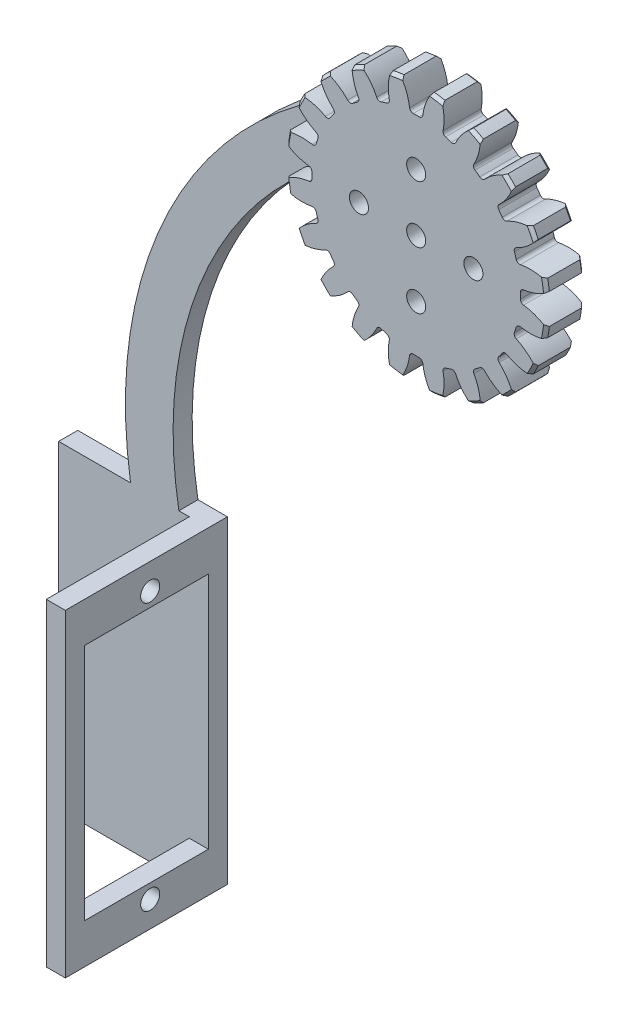
SolidWorks part; units mm, degrees
ref_plane "Front Plane" through (0, 0, 0) normal (0, 0, 1) x (1, 0, 0)
ref_plane "Top Plane" through (0, 0, 0) normal (0, 1, 0) x (1, 0, 0)
ref_plane "Right Plane" through (0, 0, 0) normal (1, 0, 0) x (0, 0, -1)
sketch "Sketch1" plane through (0, 0, 0) normal (0, 0, 1) x (1, 0, 0)
  circle A0 centre (0, 0) radius 12.5 construction
  circle A1 centre (0, 0) radius 13.75
  dimension "D1" = 25
  dimension "D2" = 27.5
extrude "Boss-Extrude1" add sketch "Sketch1" along normal blind 4 contours A1
sketch "Sketch3" plane through (0, 0, 0) normal (0, 0, 1) x (1, 0, 0)
  line L0 (0, 0) -> (0, 13.75) construction
  line L1 (0, 0) -> (-2.151, 13.5807) construction
  line L2 (0, 0) -> (2.151, 13.5807) construction
  line L3 (-2.3599, 10.6799) -> (0, 0) construction
  line L4 (-2.9181, 12.1546) -> (-0.9807, 12.4615) construction
  line L5 (-0.9807, 12.4615) -> (0.9807, 12.4615) construction
  line L6 (-3.5448, 13.2852) -> (-1.5279, 9.6467) construction
  arc A0 (-1.0558, 10.8864) -> (-2.3599, 10.6799) centre (0, 0) ccw
  circle A1 centre (0, 0) radius 11.25 construction
  circle A2 centre (0, 0) radius 13.75 construction
  arc A3 (-3.7081, 13.2406) -> (-2.3599, 10.6799) centre (-7.7122, 9.4972) cw
  circle A4 centre (0, 0) radius 13.75 construction
  arc A5 (-0.5649, 13.7384) -> (-1.0558, 10.8864) centre (4.4, 11.4156) ccw
  circle A6 centre (0, 0) radius 12.5 construction
  arc A7 (-0.5649, 13.7384) -> (-3.7081, 13.2406) centre (0, 0) ccw
  dimension "D1" = 18
  dimension "D2" = 2.5
  dimension "D3" = 2.8125
  dimension "D4" = 20
extrude "Cut-Extrude4" cut sketch "Sketch3" against normal through all and the other way through all
fillet "Fillet1" radius 0.375 2 edges at (-1.0558, 10.8864, 2) (-2.3599, 10.6799, 2)
chamfer "Chamfer1" distance 0.3125 2 edges at (2.151, -13.5807, 0) (2.151, -13.5807, 4)
pattern_circular "CirPattern1" count 20 over 360 about axis through (0, 0, 0) along (0, 0, 1) of "Cut-Extrude4", "Fillet1"
sketch "Sketch4" plane through (0, 0, 4) normal (0, 0, 1) x (1, 0, 0)
  circle A0 centre (0, 0) radius 0.5
extrude "Cut-Extrude5" cut sketch "Sketch4" against normal through all
move or copy body "Body-Move/Copy1" bodies to move or copy 105 copy no rotation origin (0, 0, 0) rotation axis (0, 0, 1) rotation angle 9
mirror "Mirror1" about plane through (0, 0, 0) normal (1, 0, 0) of bodies 108 107
delete or keep bodies "Body-Delete/Keep 1" type delete bodies bodies 108
sketch "Sketch12" plane through (0, 0, 4) normal (0, 0, 1) x (1, 0, 0)
  line L0 (0, -16.1208) -> (0, 16.4837) construction
  line L1 (3.7696, 0) -> (-5.3712, 0) construction
  circle A0 centre (0, 0) radius 1
  circle A1 centre (0, -6) radius 1
  circle A2 centre (-6, 0) radius 1
  circle A3 centre (0, 6) radius 1
  circle A4 centre (6, 0) radius 1
  point P19 (0, 0)
  dimension "D1" = 2
  dimension "D2" = 2
  dimension "D3" = 6
  dimension "D4" = 4
extrude "Cut-Extrude8" cut sketch "Sketch12" against normal up to surface (4 mm away) up to face at (-0.4938, 0.0782, 0)
sketch "Sketch13" plane through (0, 0, 0) normal (0, 0, -1) x (-1, 0, 0)
  line L0 (23.1469, 0) -> (-25.305, 0) construction
  line L1 (21.3966, -32.5) -> (-39.3897, -32.5) construction
  line L2 (-12.5, 6.7605) -> (-12.5, -41.0245) construction
  line L3 (12.5, 6.7605) -> (12.5, -41.0245) construction
  line L4 (23.8, -16.4657) -> (23.8, -36.0763) construction
  line L5 (56.7967, -39.45) -> (45.2507, -39.45) construction
  line L6 (56.7967, -44.45) -> (-42.3327, -44.45) construction
  line L7 (56.7967, -61.45) -> (-42.3327, -61.45) construction
  line L8 (56.7967, -67.85) -> (-42.3327, -67.85) construction
  line L9 (56.7967, -72.85) -> (46.151, -72.85) construction
  line L10 (39.5, -16.4657) -> (39.5, -31.1315) construction
  line L11 (23.8, -39.45) -> (26.8916, -39.45)
  line L12 (39.5, -72.85) -> (39.5, -39.45)
  line L13 (39.5, -72.85) -> (23.8, -72.85)
  line L14 (23.8, -39.45) -> (23.8, -72.85)
  line L15 (26.8916, -39.45) -> (23.8, -39.45) construction
  line L16 (56.7967, -39.45) -> (-42.3327, -39.45) construction
  line L17 (31.9601, -39.45) -> (39.5, -39.45)
  line L18 (12.5, -39.45) -> (-42.3327, -39.45) construction
  line L19 (23.8, -39.45) -> (23.8, -72.85) construction
  line L20 (23.8, -16.4657) -> (23.8, -94.9878) construction
  line L21 (39.5, -39.45) -> (39.5, -72.85) construction
  line L22 (39.5, -16.4657) -> (39.5, -94.9878) construction
  line L23 (39.5, -39.45) -> (31.9601, -39.45) construction
  line L24 (39.5, -72.85) -> (23.8, -72.85) construction
  line L25 (56.7967, -72.85) -> (-42.3327, -72.85) construction
  line L26 (7.4218, -72.85) -> (-42.3327, -72.85) construction
  line L27 (0, 5.4967) -> (0, 10.729)
  arc A0 (31.9601, -39.45) -> (0, 10.729) centre (-12.5, -32.5) ccw
  arc A1 (26.8916, -39.45) -> (0, 5.4967) centre (-12.5, -32.5) ccw
  dimension "D4" = 40
  dimension "D5" = 11.3
  dimension "D12" = 45
  dimension "D1" = 32.5
  dimension "D2" = 25
  dimension "D3" = 12.5
  dimension "D6" = 39.45
  dimension "D10" = 5
  dimension "D7" = 5
  dimension "D8" = 17
  dimension "D9" = 6.4
  dimension "D11" = 15.7
extrude "Boss-Extrude2" add sketch "Sketch13" against normal blind 2
sketch "Sketch14" plane through (0, 0, 2) normal (0, 0, 1) x (1, 0, 0)
  line L1 (-23.8, -39.45) -> (-25.8, -39.45)
  line L2 (-23.8, -39.45) -> (-23.8, -72.85)
  line L3 (-23.8, -72.85) -> (-25.8, -72.85)
  line L4 (-25.8, -39.45) -> (-25.8, -72.85)
  line L5 (-23.8, -39.45) -> (-25.8, -72.85) construction
  line L6 (-23.8, -72.85) -> (-25.8, -39.45) construction
  point P4 (-24.8, -56.15)
  dimension "D1" = 33.4
  dimension "D2" = 2
extrude "Boss-Extrude3" add sketch "Sketch14" along normal blind 15
sketch "Sketch15" plane through (-23.8, 0, 0) normal (1, 0, 0) x (0, 0, -1)
  line L0 (-17, -39.45) -> (0, -39.45) construction
  line L1 (-15, -68.65) -> (-2, -68.65)
  line L2 (-15, -68.65) -> (-15, -43.65)
  line L3 (-15, -43.65) -> (-2, -43.65)
  line L4 (-2, -68.65) -> (-2, -43.65)
  line L5 (-15, -68.65) -> (-2, -43.65) construction
  line L6 (-15, -43.65) -> (-2, -68.65) construction
  line L7 (0, -39.45) -> (0, -72.85) construction
  line L9 (-17.5917, -56.15) -> (1.935, -56.15) construction
  line L10 (-8.1, -74.2819) -> (-8.1, -36.0877) construction
  circle A0 centre (-8.1, -42.15) radius 1
  circle A1 centre (-8.1, -70.15) radius 1
  point P4 (-8.5, -56.15)
  dimension "D5" = 2
  dimension "D1" = 25
  dimension "D2" = 13
  dimension "D3" = 4.2
  dimension "D4" = 2
  dimension "D6" = 6.1
  dimension "D7" = 14
extrude "Cut-Extrude9" cut sketch "Sketch15" against normal up to surface (2 mm away)
sketch "Sketch16" plane through (0, 0, 0) normal (0, 0, -1) x (-1, 0, 0)
  circle A0 centre (0, 6) radius 1
extrude "Cut-Extrude10" cut sketch "Sketch16" against normal up to surface (2 mm away)
equation "\"Module\"= 1.25mm"
equation "\"#teeths\"= 20"
equation "\"Pressure Angle\"= 20"
equation "\"D1@Sketch1\"=\"Module\" * \"#teeths\""
equation "\"D2@Sketch1\"=(\"#teeths\" + 2) * \"Module\""
equation "\"D1@Fillet1\"=0.3 *\"Module\""
equation "\"D1@CirPattern1\"=\"#teeths\""
equation "\"D1@Chamfer1\"=\"Module\" /4"
